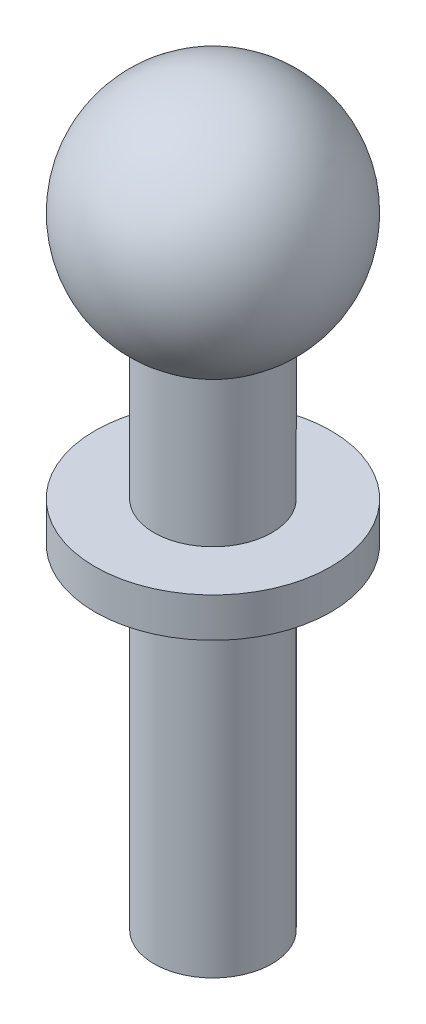
SolidWorks part; units mm, degrees
other "Cable Anchor Ball Stud"
ref_plane "Front Plane" through (0, 0, 0) normal (0, 0, 1) x (1, 0, 0)
ref_plane "Top Plane" through (0, 0, 0) normal (0, 1, 0) x (1, 0, 0)
ref_plane "Right Plane" through (0, 0, 0) normal (1, 0, 0) x (0, 0, -1)
sketch3d "M3 neck and thread envelope sketch datum points"
  point P0 (-23.3827, -90, -19)
  point P1 (-13.3827, -90, -19)
  point P2 (-23.3827, -90, -9)
ref_plane "M3 neck and thread envelope sketch plane" through (0, -90, 0) normal (0, -1, 0) x (-1, 0, 0)
sketch "M3 neck and thread envelope sketch" plane through (0, -90, 0) normal (0, -1, 0) x (-1, 0, 0)
  circle A0 centre (23.3827, 19) radius 1.5
extrude "M3 neck and thread envelope" add sketch "M3 neck and thread envelope sketch" along normal blind 15.8 separate body
sketch3d "Six millimetre anchor ball axis line"
  line L0 (-23.3827, -90, -29) -> (-23.3827, -90, -9) construction
ref_axis "Six millimetre anchor ball axis" through (-23.3827, -90, -29) along (0, 0, 1)
sketch3d "Six millimetre anchor ball profile datum points"
  point P0 (-23.3827, -90, -19)
  point P1 (-13.3827, -90, -19)
  point P2 (-23.3827, -90, -9)
ref_plane "Six millimetre anchor ball profile plane" through (0, -90, 0) normal (0, -1, 0) x (-1, 0, 0)
sketch "Six millimetre anchor ball profile" plane through (0, -90, 0) normal (0, -1, 0) x (-1, 0, 0)
  line L0 (23.3827, 16) -> (23.3827, 22)
  arc A0 (23.3827, 22) -> (23.3827, 16) centre (23.3827, 19) ccw
revolve "Six millimetre anchor ball" add sketch "Six millimetre anchor ball profile" angle 360 about axis through (-23.3827, -90, -29) along (0, 0, 1)
sketch3d "Anchor seating collar sketch datum points"
  point P0 (-23.3827, -96.3, -19)
  point P1 (-13.3827, -96.3, -19)
  point P2 (-23.3827, -96.3, -9)
ref_plane "Anchor seating collar sketch plane" through (0, -96.3, 0) normal (0, -1, 0) x (-1, 0, 0)
sketch "Anchor seating collar sketch" plane through (0, -96.3, 0) normal (0, -1, 0) x (-1, 0, 0)
  circle A0 centre (23.3827, 19) radius 3
extrude "Anchor seating collar" add sketch "Anchor seating collar sketch" along normal blind 1
sketch3d "Anchor tail hex drive sketch datum points"
  point P0 (-23.3827, -105.9, -19)
  point P1 (-13.3827, -105.9, -19)
  point P2 (-23.3827, -105.9, -29)
ref_plane "Anchor tail hex drive sketch plane" through (0, -105.9, 0) normal (0, 1, 0) x (1, 0, 0)
sketch "Anchor tail hex drive sketch" plane through (0, -105.9, 0) normal (0, 1, 0) x (1, 0, 0)
  line L0 (-22.5167, 19) -> (-22.9497, 19.75)
  line L1 (-22.9497, 19.75) -> (-23.8157, 19.75)
  line L2 (-23.8157, 19.75) -> (-24.2487, 19)
  line L3 (-24.2487, 19) -> (-23.8157, 18.25)
  line L4 (-23.8157, 18.25) -> (-22.9497, 18.25)
  line L5 (-22.9497, 18.25) -> (-22.5167, 19)
  circle A0 centre (-23.3827, 19) radius 0.866 construction
extrude "Anchor tail hex drive" cut sketch "Anchor tail hex drive sketch" along normal blind 1.6
